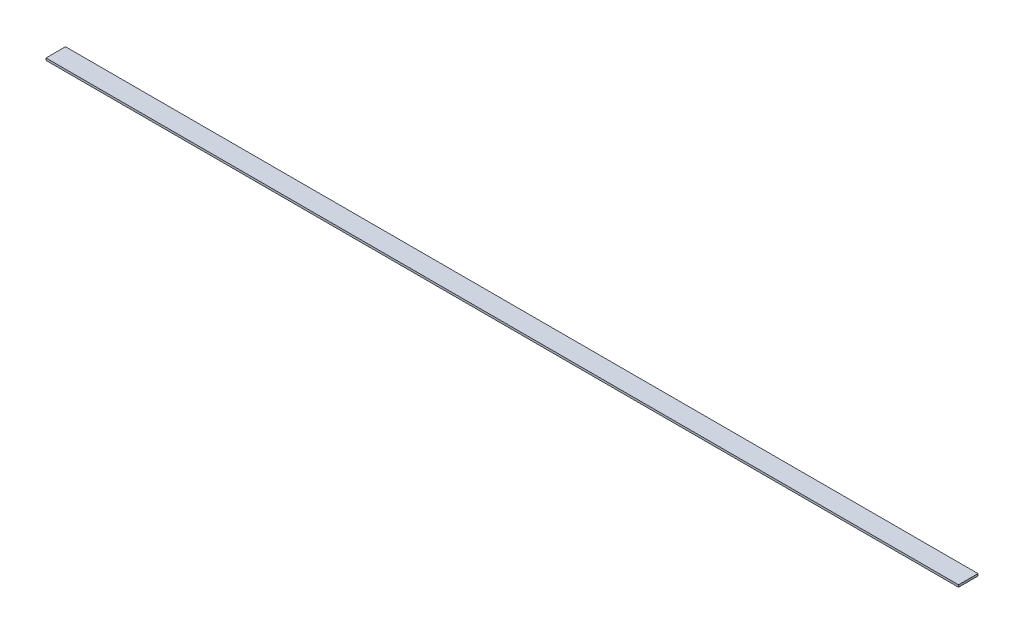
SolidWorks part; units mm, degrees
ref_plane "Front Plane" through (0, 0, 0) normal (0, 0, 1) x (1, 0, 0)
ref_plane "Top Plane" through (0, 0, 0) normal (0, 1, 0) x (1, 0, 0)
ref_plane "Right Plane" through (0, 0, 0) normal (1, 0, 0) x (0, 0, -1)
sketch "Sketch1" plane through (0, 0, 0) normal (0, 1, 0) x (1, 0, 0)
  line L1 (-527.5, 11.25) -> (527.5, 11.25)
  line L2 (-527.5, 11.25) -> (-527.5, -11.25)
  line L3 (-527.5, -11.25) -> (527.5, -11.25)
  line L4 (527.5, 11.25) -> (527.5, -11.25)
  line L5 (-527.5, 11.25) -> (527.5, -11.25) construction
  line L6 (-527.5, -11.25) -> (527.5, 11.25) construction
  point P0 (0, 0)
  dimension "D1" = 1055
  dimension "D2" = 22.5
extrude "Boss-Extrude1" add sketch "Sketch1" along normal blind 2.5
